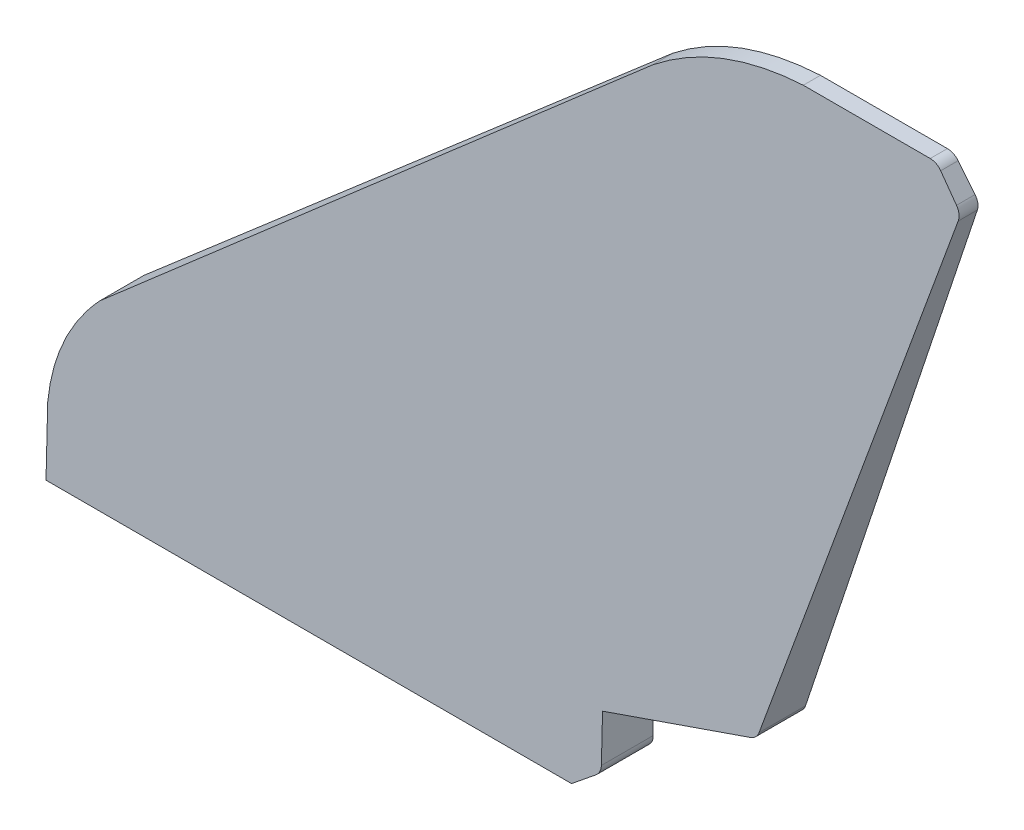
SolidWorks part; units mm, degrees
ref_plane "Front Plane" through (0, 0, 0) normal (0, 0, 1) x (1, 0, 0)
ref_plane "Top Plane" through (0, 0, 0) normal (0, 1, 0) x (1, 0, 0)
ref_plane "Right Plane" through (0, 0, 0) normal (1, 0, 0) x (0, 0, -1)
sketch "Sketch2" plane through (0, 0, 0) normal (0, 1, 0) x (1, 0, 0)
  line L0 (200, 464) -> (1000, 464) construction
  line L1 (598.4496, 547.161) -> (7944.0994, 568.2387) construction
  line L2 (742.0822, 604.451) -> (2551.2848, 871.4627)
  line L3 (2551.2848, 871.4627) -> (6740.738, 635.7302)
  line L4 (6740.738, 635.7302) -> (6740.738, 471.3893)
  line L5 (6740.738, 471.3893) -> (2552.6168, 213.0704)
  line L6 (2552.6168, 213.0704) -> (742.0822, 470.8955)
  line L7 (742.0822, 470.8955) -> (742.0822, 604.451)
  point P10 (742.0822, 537.6733)
  dimension "D1" = 7345.68
  dimension "D2" = 6.75
  dimension "D3" = 4196.08
  dimension "D4" = 4196.08
  dimension "D5" = 1828.8
  dimension "D6" = 1828.8
  dimension "D7" = 16.5
ref_plane "Plane1" through (0, 8019.288, 0) normal (0, 1, 0) x (1, 0, 0)
sketch "Sketch4" plane through (0, 8019.288, 0) normal (0, 1, 0) x (1, 0, 0)
  line L0 (9633.218, 637.9418) -> (9179.138, 572.1033)
  line L1 (9179.138, 572.1033) -> (9179.138, 536.2304)
  line L2 (10703.138, 533.4884) -> (10703.138, 574.8453)
  line L3 (10703.138, 574.8453) -> (9633.218, 637.9418)
  line L4 (9179.138, 554.1668) -> (10703.138, 554.1668) construction
  line L5 (10703.138, 533.4884) -> (9633.218, 470.3919)
  line L6 (9633.218, 470.3919) -> (9179.138, 536.2304)
  line L8 (6740.738, 635.7302) -> (6740.738, 471.3893) construction
  dimension "D1" = 6.75
  dimension "D2" = 16.5
  dimension "D3" = 17.9365
  dimension "D4" = 1524
  dimension "D5" = 2438.4
ref_plane "Plane2" through (0, 0, -537.6733) normal (0, 0, 1) x (1, 0, 0)
sketch "Sketch5" plane through (0, 0, -537.6733) normal (0, 0, 1) x (1, 0, 0)
  line L0 (742.0822, 0) -> (742.0822, 764.5745)
  line L1 (1302.621, 2026.4445) -> (7478.5399, 7379.6459)
  line L2 (9633.218, 8019.288) -> (9179.138, 8019.288) construction
  line L3 (6740.738, 0) -> (7072.278, 267.7431)
  line L4 (6740.738, 0) -> (2552.6168, 0) construction
  line L5 (7072.278, 267.7431) -> (7072.278, 870.7026)
  line L6 (7072.278, 870.7026) -> (8816.7983, 1464.0217)
  line L7 (8816.7983, 1464.0217) -> (10985.7445, 7649.3251)
  line L9 (10703.138, 8019.288) -> (10985.7445, 7649.3251)
  line L10 (9179.138, 8019.288) -> (10703.138, 8019.288)
  line L11 (10703.138, 8019.288) -> (9633.218, 8019.288) construction
  line L12 (742.0822, 0) -> (6740.738, 0)
  spline S0 degree 2 poles (742.0822, 764.5745) (796.7915, 1480.7594) (1302.621, 2026.4445) knots 0 0 0 1 1 1
  spline S1 degree 2 poles (9179.138, 8019.288) (8219.3195, 7966.6148) (7478.5399, 7379.6459) knots 0 0 0 1 1 1
extrude "Boss-Extrude1" add sketch "Sketch5" along normal mid plane 609.6
sketch "Sketch7" plane through (742.0822, 0, 0) normal (-1, 0, 0) x (0, 0, 1)
  line L0 (-842.4733, 0) -> (-635.7302, 8019.288)
  line L1 (-232.8733, 8019.288) -> (-842.4733, 8019.288) construction
  line L2 (-635.7302, 8019.288) -> (-439.6163, 8019.288)
  line L3 (-439.6163, 8019.288) -> (-232.8733, 0)
  line L5 (-537.6733, -4410.6084) -> (-537.6733, 4410.6084) construction
  line L6 (-439.6163, 8019.288) -> (55.6563, 8019.288)
  line L7 (55.6563, 8019.288) -> (0, 0)
  line L8 (0, 0) -> (-232.8733, 0)
  line L9 (-635.7302, 8019.288) -> (-1159.1084, 8019.288)
  line L10 (-1159.1084, 8019.288) -> (-1159.1084, 0)
  line L11 (-1159.1084, 0) -> (-842.4733, 0)
  point P5 (-537.6733, 8019.288)
extrude "Cut-Extrude2" cut sketch "Sketch7" against normal through all both and the other way through all contours L6 L7 L8 L3 | L9 L10 L11 L0
fillet "Fillet1" radius 152.4 1 edges at (10703.138, 8019.288, -537.6733)
fillet "Fillet2" radius 152.4 1 edges at (10985.7445, 7649.3251, -537.6733)
fillet "Fillet3" radius 152.4 1 edges at (8816.7983, 1464.0217, -537.6733)
fillet "Fillet4" radius 152.4 1 edges at (7072.278, 267.7431, -537.6733)
